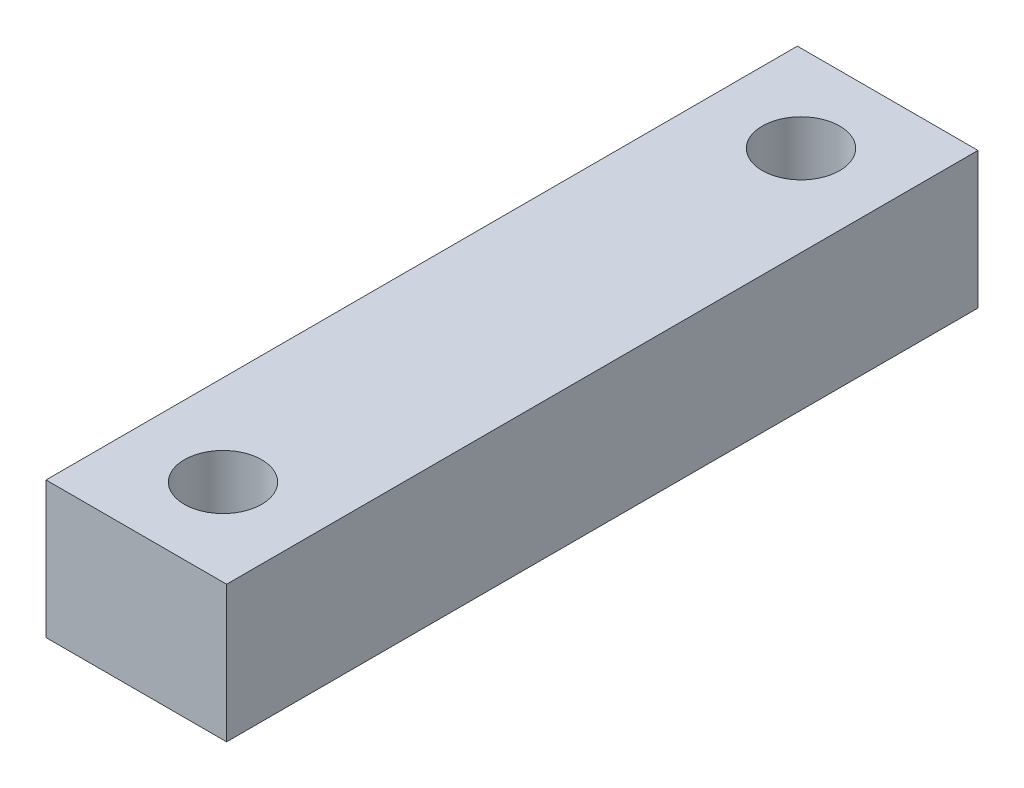
SolidWorks part; units mm, degrees
material "1060 Alloy"
ref_plane "Frontal Plane" through (0, 0, 0) normal (0, 0, 1) x (1, 0, 0)
ref_plane "Horizontal Plane" through (0, 0, 0) normal (0, 1, 0) x (1, 0, 0)
ref_plane "Profile Plane" through (0, 0, 0) normal (1, 0, 0) x (0, 0, -1)
sketch "Sketch1" plane through (0, 0, 0) normal (0, 1, 0) x (1, 0, 0)
  line L1 (-9.9219, 41.275) -> (9.9219, 41.275)
  line L2 (-9.9219, 41.275) -> (-9.9219, -41.275)
  line L3 (-9.9219, -41.275) -> (9.9219, -41.275)
  line L4 (9.9219, 41.275) -> (9.9219, -41.275)
  line L5 (-9.9219, 41.275) -> (9.9219, -41.275) construction
  line L6 (-9.9219, -41.275) -> (9.9219, 41.275) construction
  circle A0 centre (0, -31.75) radius 4.25
  circle A1 centre (0, 31.75) radius 4.25
  point P0 (0, 0)
  dimension "D3" = 8.5
  dimension "D1" = 82.55
  dimension "D2" = 19.8438
  dimension "D4" = 63.5
  dimension "D5" = 31.75
extrude "Boss-Extrude1" add sketch "Sketch1" along normal blind 15
